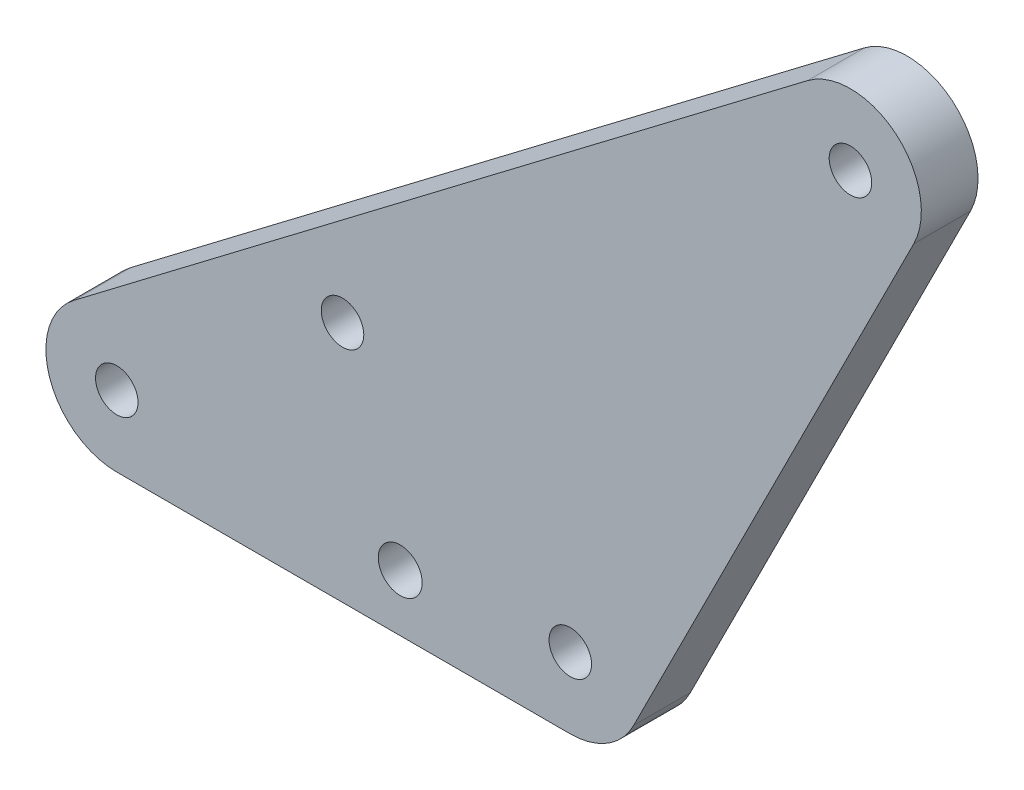
SolidWorks part; units mm, degrees
material "PMMA"
ref_plane "前视基准面" through (0, 0, 0) normal (0, 0, 1) x (1, 0, 0)
ref_plane "上视基准面" through (0, 0, 0) normal (0, 1, 0) x (1, 0, 0)
ref_plane "右视基准面" through (0, 0, 0) normal (1, 0, 0) x (0, 0, -1)
other "Configuration Table"
sketch "草图1" plane through (0, 0, 0) normal (0, 0, 1) x (1, 0, 0)
  line L0 (15.8503, 25.0217) -> (-35.9153, -14.2889) construction
  line L1 (-35.9153, -14.2889) -> (-3.9153, -14.2889) construction
  line L2 (-3.9153, -14.2889) -> (15.8503, 25.0217) construction
  line L3 (12.8264, 29.0036) -> (-38.9392, -10.3069)
  line L4 (-35.9153, -19.2889) -> (-3.9153, -19.2889)
  line L5 (0.5518, -16.535) -> (20.3174, 22.7756)
  line L6 (-50.767, -19.2889) -> (-0.8329, -19.2889) construction
  line L7 (30.0102, 42.0529) -> (-50.767, -19.2889) construction
  line L8 (-0.8329, -19.2889) -> (30.0102, 42.0529) construction
  arc A0 (-35.9153, -19.2889) -> (-38.9392, -10.3069) centre (-35.9153, -14.2889) cw
  arc A1 (-3.9153, -19.2889) -> (0.5518, -16.535) centre (-3.9153, -14.2889) ccw
  arc A2 (20.3174, 22.7756) -> (12.8264, 29.0036) centre (15.8503, 25.0217) ccw
  circle A3 centre (15.8503, 25.0217) radius 1.5
  circle A4 centre (-3.9153, -14.2889) radius 1.5
  circle A5 centre (-35.9153, -14.2889) radius 1.5
  circle A6 centre (-19.9875, -2.1933) radius 1.5
  circle A7 centre (-15.9153, -15.2889) radius 1.55
  dimension "D5" = 5
  dimension "D6" = 3
  dimension "D7" = 3
  dimension "D8" = 3
  dimension "D9" = 3
  dimension "D13" = 3.1
  dimension "D1" = 65
  dimension "D2" = 32
  dimension "D3" = 44
  dimension "D10" = 45
  dimension "D11" = 12
  dimension "D12" = 4
  dimension "D4" = 5
extrude "凸台-拉伸1" add sketch "草图1" along normal blind 4
